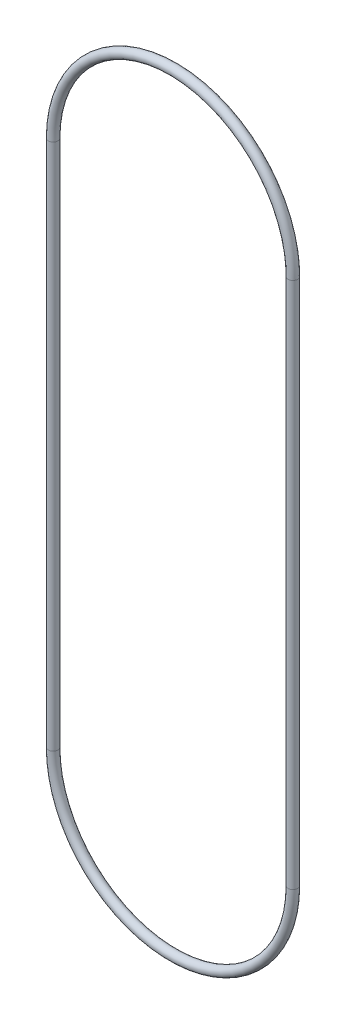
SolidWorks part; units mm, degrees
ref_plane "Front Plane" through (0, 0, 0) normal (0, 0, 1) x (1, 0, 0)
ref_plane "Top Plane" through (0, 0, 0) normal (0, 1, 0) x (1, 0, 0)
ref_plane "Right Plane" through (0, 0, 0) normal (1, 0, 0) x (0, 0, -1)
sketch "Sketch1" plane through (0, 0, 0) normal (0, 0, 1) x (1, 0, 0)
  line L0 (1.25, 0) -> (1.25, -5.5)
  line L1 (-1.25, 0) -> (-1.25, -5.5)
  arc A0 (1.25, 0) -> (-1.25, 0) centre (0, 0) ccw
  arc A1 (-1.25, -5.5) -> (1.25, -5.5) centre (0, -5.5) ccw
  dimension "D1" = 1.25
  dimension "D3" = 5.5
sketch "Sketch3" plane through (0, 0, 0) normal (0, 1, 0) x (1, 0, 0)
  circle A0 centre (1.25, 0) radius 0.05
  dimension "D1" = 0.1
sweep "Sweep5" add profiles "Sketch3" path "Sketch1"
